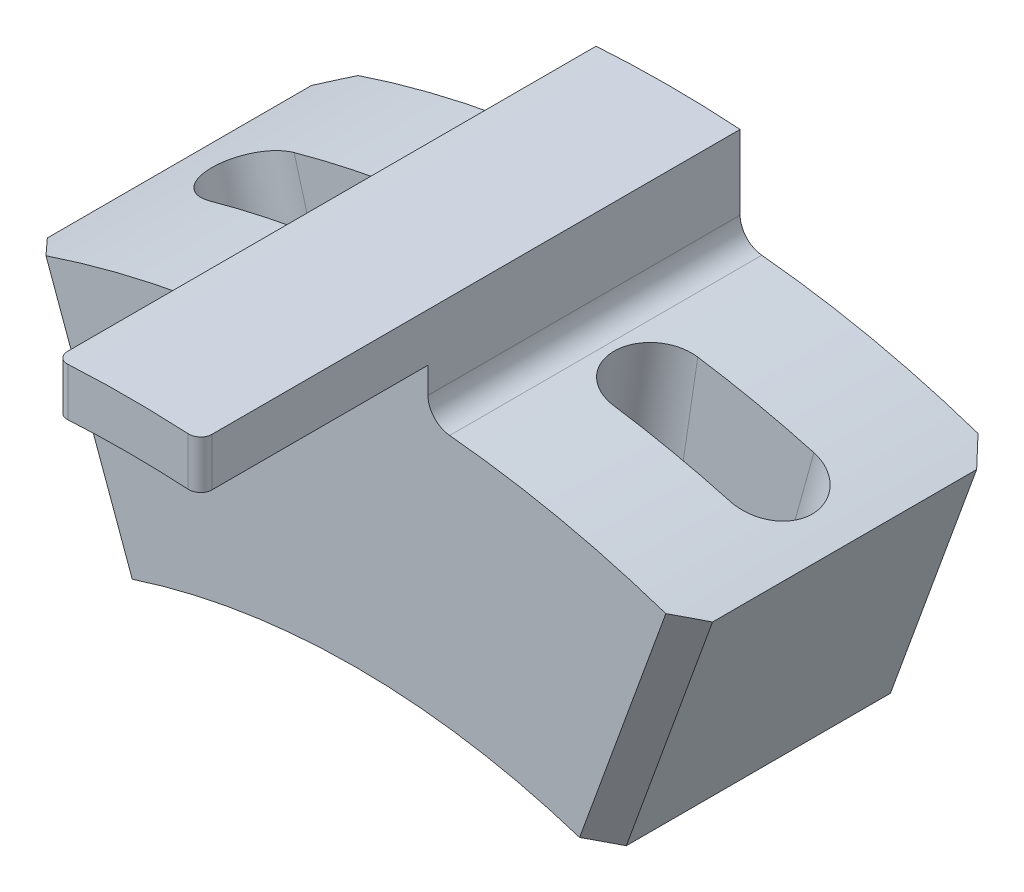
SolidWorks part; units mm, degrees
material "PETG"
ref_plane "Спереди" through (0, 0, 0) normal (0, 0, 1) x (1, 0, 0)
ref_plane "Сверху" through (0, 0, 0) normal (0, 1, 0) x (1, 0, 0)
ref_plane "Справа" through (0, 0, 0) normal (1, 0, 0) x (0, 0, -1)
sketch "Эскиз1" plane through (0, 0, 0) normal (0, 0, 1) x (1, 0, 0)
  line L0 (10.2606, 28.1908) -> (13.8518, 38.0576)
  line L1 (-10.2606, 28.1908) -> (-13.8518, 38.0576)
  line L2 (0, 0) -> (0, 84.5239) construction
  line L3 (-3, 44.3988) -> (-3, 40.3887)
  line L4 (3, 44.3988) -> (3, 40.3887)
  arc A0 (10.2606, 28.1908) -> (-10.2606, 28.1908) centre (0, 0) ccw
  arc A1 (3, 44.3988) -> (-3, 44.3988) centre (0, 0) ccw
  arc A2 (13.8518, 38.0576) -> (3, 40.3887) centre (0, 0) ccw
  circle A3 centre (0, 0) radius 44.5 construction
  circle A4 centre (0, 0) radius 30 construction
  arc A5 (-3, 40.3887) -> (-13.8518, 38.0576) centre (0, 0) ccw
  arc A7 (13.8518, 38.0576) -> (-13.8518, 38.0576) centre (0, 0) ccw construction
  point P6 (59.769, 18.2732)
  point P7 (70, 0)
  dimension "D1" = 60
  dimension "D4" = 10.5
  dimension "D3" = 20
  dimension "D5" = 6
  dimension "D2" = 14.5
extrude "Бобышка-Вытянуть1" add sketch "Эскиз1" along normal mid plane 13
sketch "Эскиз2" plane through (0, 0, 6.5) normal (0, 0, 1) x (1, 0, 0)
  line L0 (3, 40.3887) -> (3, 44.3988) construction
  line L1 (-3, 44.3988) -> (-3, 40.3887) construction
  line L2 (3, 42.394) -> (3, 44.3988)
  line L3 (-3, 44.3988) -> (-3, 42.394)
  arc A0 (3, 44.3988) -> (-3, 44.3988) centre (0, 0) ccw construction
  arc A1 (3, 44.3988) -> (-3, 44.3988) centre (0, 0) ccw
  arc A2 (2.8652, 42.4033) -> (-2.8652, 42.4033) centre (0, 0) ccw construction
  arc A6 (3, 42.394) -> (-3, 42.394) centre (0, 0) ccw
  dimension "D1" = 2
extrude "Бобышка-Вытянуть2" add sketch "Эскиз2" along normal blind 9.5
sketch "Эскиз4" plane through (0, 0, 0) normal (0, 0, 1) x (1, 0, 0)
  line L0 (0, 0) -> (10.8232, 39.027) construction
  line L1 (13.7121, 42.8957) -> (8.3673, 23.6231)
  line L4 (8.3673, 23.6231) -> (6.681, 24.0908)
  line L5 (13.7121, 42.8957) -> (12.0257, 43.3634)
  line L6 (6.681, 24.0908) -> (12.0257, 43.3634)
  line L7 (0, 0) -> (0, 30) construction
  arc A0 (13.8518, 38.0576) -> (3, 40.3887) centre (0, 0) ccw construction
  arc A1 (10.2606, 28.1908) -> (-10.2606, 28.1908) centre (0, 0) ccw construction
  dimension "D1" = 3.5
  dimension "D2" = 15.5
  dimension "D3" = 25
  dimension "D4" = 20
  dimension "D5" = 1.4276
revolve "Вырез-Повернуть1" cut sketch "Эскиз4" angle 360 about L0
pattern_circular "Круговой массив1" count 2 every 7 about axis through (0, 0, 6.5) along (0, 0, -1) of "Вырез-Повернуть1"
sketch "Эскиз6" plane through (0, 0, 0) normal (0, 0, 1) x (1, 0, 0)
  line L0 (4.4343, 29.6705) -> (5.9863, 40.0551)
  line L1 (8.0172, 28.9089) -> (10.8232, 39.027)
  arc A0 (10.2606, 28.1908) -> (-10.2606, 28.1908) centre (0, 0) ccw construction
  arc A1 (13.8518, 38.0576) -> (3, 40.3887) centre (0, 0) ccw construction
  arc A2 (8.0172, 28.9089) -> (4.4343, 29.6705) centre (0, 0) ccw
  arc A3 (10.8232, 39.027) -> (5.9863, 40.0551) centre (0, 0) ccw
  arc A5 (6.1575, 29.3613) -> (2.696, 29.8786) centre (0, 0) ccw construction
  arc A6 (9.6899, 28.392) -> (6.3171, 29.3274) centre (0, 0) ccw construction
  arc A10 (7.7115, 39.7591) -> (4.2499, 40.2764) centre (0, 0) ccw construction
  arc A12 (12.4994, 38.5229) -> (9.1267, 39.4582) centre (0, 0) ccw construction
extrude "Вырез-Вытянуть2" cut sketch "Эскиз6" against normal mid plane 3.5
mirror "Зеркальное отражение1" about plane through (0, 0, 0) normal (1, 0, 0) of "Вырез-Вытянуть2", "Круговой массив1", "Вырез-Повернуть1"
fillet "Скругление1" radius 1 2 edges at (-3, 40.3887, 0) (3, 40.3887, 0)
chamfer "Фаска1" distance 1 angle 45 4 edges at (12.0562, 33.1242, 6.5) (-12.0562, 33.1242, 6.5) (-12.0562, 33.1242, -6.5) (12.0562, 33.1242, -6.5)
fillet "Скругление2" radius 0.5 2 edges at (3, 43.3964, 16) (-3, 43.3964, 16)
